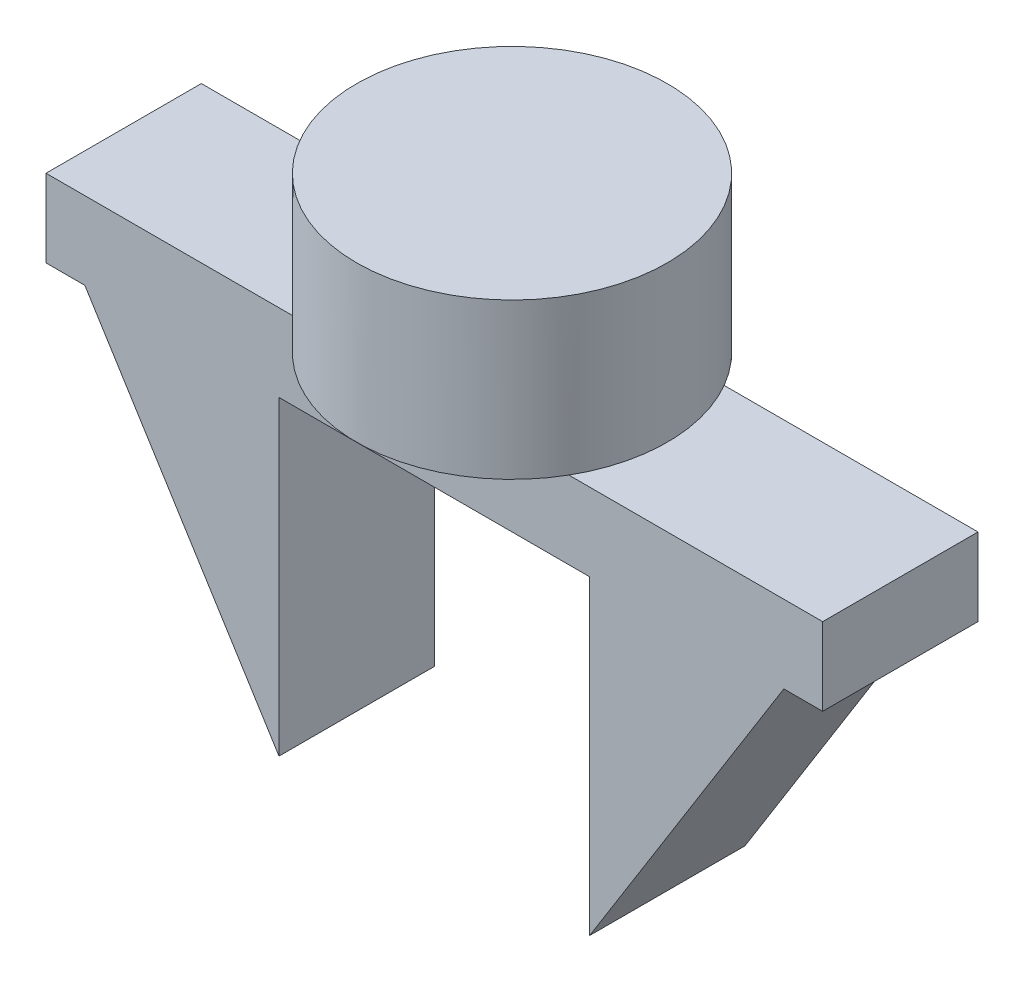
SolidWorks part; units mm, degrees
ref_plane "前视基准面" through (0, 0, 0) normal (0, 0, 1) x (1, 0, 0)
ref_plane "上视基准面" through (0, 0, 0) normal (0, 1, 0) x (1, 0, 0)
ref_plane "右视基准面" through (0, 0, 0) normal (1, 0, 0) x (0, 0, -1)
other "Configuration Table"
sketch "草图2" plane through (0, 0, 0) normal (0, 0, 1) x (1, 0, 0)
  line L0 (50, 0) -> (-50, 0)
  line L1 (-50, 0) -> (-50, -10)
  line L2 (-50, -10) -> (-45, -10)
  line L3 (-45, -10) -> (-20, -50)
  line L4 (-20, -50) -> (-20, -10)
  line L5 (-20, -10) -> (20, -10)
  line L7 (20, -50) -> (20, -10)
  line L8 (45, -10) -> (20, -50)
  line L9 (50, -10) -> (45, -10)
  line L10 (50, 0) -> (50, -10)
  dimension "D2" = 10
  dimension "D4" = 5
  dimension "D5" = 40
  dimension "D6" = 10
extrude "凸台-拉伸1" add sketch "草图2" along normal blind 20
sketch "草图3" plane through (0, 0, 0) normal (0, 1, 0) x (1, 0, 0)
  line L0 (-50, -10) -> (50, -10) construction
  line L1 (-50, -20) -> (-50, 0) construction
  line L2 (50, -20) -> (50, 0) construction
  circle A0 centre (0, -10) radius 20
  dimension "D1" = 40
extrude "凸台-拉伸2" add sketch "草图3" along normal blind 20
